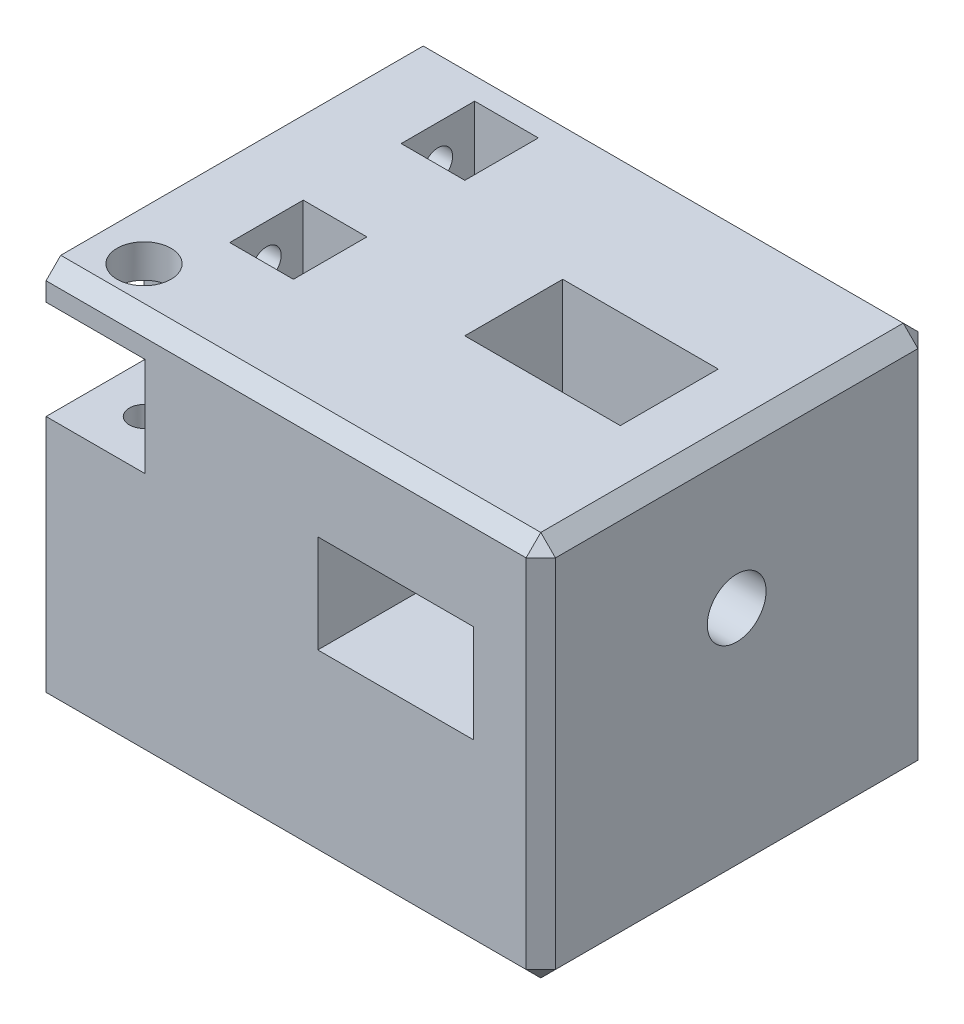
SolidWorks part; units mm, degrees
ref_plane "Front Plane" through (0, 0, 0) normal (1, 0, 0) x (0, 1, 0)
ref_plane "Top Plane" through (0, 0, 0) normal (0, 0, 1) x (0, 1, 0)
ref_plane "Right Plane" through (0, 0, 0) normal (0, 1, 0) x (-1, 0, 0)
sketch "Sketch1" plane through (0, 0, 0) normal (1, 0, 0) x (0, 1, 0)
  line L1 (-640.9609, 1222.3293) -> (-562.1826, 1222.3293)
  line L2 (-640.9609, 1222.3293) -> (-640.9609, 1142.3293)
  line L3 (-640.9609, 1142.3293) -> (-562.1826, 1142.3293)
  line L4 (-562.1826, 1222.3293) -> (-562.1826, 1142.3293)
  line L5 (-640.9609, 1794.8731) -> (-640.9609, 1906.8731) construction
  line L6 (-519.5399, 1142.3293) -> (-1295.5399, 1142.3293) construction
  line L7 (-562.1826, 1906.8731) -> (-562.1826, 1794.8731) construction
  dimension "D1" = 20
extrude "Boss-Extrude1" add sketch "Sketch1" along normal blind 45
sketch "Sketch2" plane through (0, 0, 1222.3293) normal (0, 0, 1) x (1, 0, 0)
  line L4 (0, -562.1826) -> (0, -640.9609)
  line L5 (0, -640.9609) -> (45, -640.9609)
  line L6 (45, -640.9609) -> (45, -562.1826)
  line L7 (45, -562.1826) -> (0, -562.1826)
  line L8 (0, -562.1826) -> (0, -640.9609)
  line L9 (0, -640.9609) -> (45, -640.9609) construction
  line L10 (45, -640.9609) -> (45, -562.1826) construction
  line L11 (45, -562.1826) -> (0, -562.1826) construction
  line L12 (0, -568.9825) -> (20.2, -568.9825)
  line L13 (0, -568.9825) -> (0, -589.1825)
  line L14 (0, -589.1825) -> (20.2, -589.1825)
  line L15 (20.2, -568.9825) -> (20.2, -589.1825)
  dimension "D2" = 20.2
  dimension "D3" = 20.2
  dimension "D1" = 0
extrude "Cut-Extrude1" cut sketch "Sketch2" against normal blind 20 contours L15 L12 L8 L14
sketch "Sketch3" plane through (0, -562.1826, 0) normal (0, 1, 0) x (-1, 0, 0)
  line L0 (-45, 1222.3293) -> (0, 1222.3293) construction
  line L1 (-11.1022, 1202.3293) -> (-8.8978, 1222.2368) construction
  line L2 (-10, 1252.7778) -> (-10, 1171.7883) construction
  line L5 (-11.1022, 1202.3293) -> (-8.8978, 1202.3293)
  line L6 (-8.8978, 1202.3293) -> (-8.8978, 1811.9293)
  line L7 (-8.8978, 1811.9293) -> (-11.1022, 1811.9293)
  line L8 (-11.1022, 1811.9293) -> (-11.1022, 1202.3293)
  line L9 (-11.1022, 1202.3293) -> (-8.8978, 1202.3293)
  line L10 (-8.8978, 1202.3293) -> (-8.8978, 1811.9293)
  line L11 (-8.8978, 1811.9293) -> (-11.1022, 1811.9293)
  line L12 (-11.1022, 1811.9293) -> (-11.1022, 1202.3293)
  circle A0 centre (-10, 1212.3293) radius 3
  point P12 (-10, 1212.283)
  dimension "D1" = 6
  dimension "D2" = 10
  dimension "D3" = 0
extrude "Cut-Extrude2" cut sketch "Sketch3" against normal through all both and the other way through all contours L12 A0 | L12 A0 L10 | L10 A0
sketch "Sketch4" plane through (45, 0, 0) normal (1, 0, 0) x (0, 1, 0)
  line L4 (-640.9609, 1222.3293) -> (-640.9609, 1142.3293)
  line L5 (-640.9609, 1142.3293) -> (-562.1826, 1142.3293)
  line L6 (-562.1826, 1142.3293) -> (-562.1826, 1222.3293)
  line L7 (-562.1826, 1222.3293) -> (-640.9609, 1222.3293)
  line L8 (-640.9609, 1222.3293) -> (-640.9609, 1142.3293)
  line L9 (-640.9609, 1142.3293) -> (-562.1826, 1142.3293)
  line L10 (-562.1826, 1142.3293) -> (-562.1826, 1222.3293)
  line L15 (-562.1826, 1222.3293) -> (-640.9609, 1222.3293)
  dimension "D1" = 0
extrude "Boss-Extrude2" add sketch "Sketch4" along normal blind 56
sketch "Sketch5" plane through (101, 0, 0) normal (1, 0, 0) x (0, 1, 0)
  circle A0 centre (-592.5449, 1182.3293) radius 10
extrude "Cut-Extrude3" cut sketch "Sketch5" against normal up to surface and the other way through all
ref_plane "Plane1" through (57.2302, 0, 0) normal (-1, 0, 0) x (0, -1, 0)
sketch "Sketch6" plane through (57.2302, 0, 0) normal (-1, 0, 0) x (0, -1, 0)
  circle A0 centre (592.5449, 1182.3293) radius 3.4
  dimension "D1" = 6.8
extrude "Boss-Extrude3" add sketch "Sketch6" along normal blind 12
sketch "Sketch7" plane through (50.4802, 0, 0) normal (1, 0, 0) x (0, 1, 0)
  circle A1 centre (-592.5449, 1182.3293) radius 10
  circle A2 centre (-592.5449, 1182.3293) radius 10
  dimension "D1" = 0
extrude "Boss-Extrude4" add sketch "Sketch7" along normal blind 5
ref_plane "Plane2" through (85.7302, 0, 0) normal (1, 0, 0) x (0, 1, 0)
sketch "Sketch8" plane through (85.7302, 0, 0) normal (1, 0, 0) x (0, 1, 0)
  circle A0 centre (-592.5449, 1182.3293) radius 3.4
extrude "Boss-Extrude5" add sketch "Sketch8" along normal blind 1.5 separate body
sketch "Sketch9" plane through (87.2302, 0, 0) normal (1, 0, 0) x (0, 1, 0)
  circle A0 centre (-592.5449, 1182.3293) radius 10
extrude "Boss-Extrude6" add sketch "Sketch9" along normal up to surface (13.7698 mm away)
sketch "Sketch10" plane through (0, 0, 1222.3293) normal (0, 0, 1) x (1, 0, 0)
  line L0 (87.4802, -585.1449) -> (51.7302, -600.2949) construction
  line L1 (51.4802, -600.0449) -> (51.9802, -600.5449) construction
  line L2 (49.9802, -581.5599) -> (49.9802, -603.5299) construction
  line L3 (89.2302, -602.7199) -> (49.9802, -602.7199)
  line L4 (89.2302, -602.7199) -> (89.2302, -582.7199)
  line L5 (89.2302, -582.7199) -> (49.9802, -582.7199)
  line L6 (49.9802, -602.7199) -> (49.9802, -582.7199)
  line L7 (89.2302, -602.7199) -> (49.9802, -582.7199) construction
  line L8 (89.2302, -582.7199) -> (49.9802, -602.7199) construction
  line L10 (55.4802, -582.7199) -> (49.9802, -582.7199)
  line L11 (55.4802, -582.7199) -> (55.4802, -602.7199)
  line L12 (55.4802, -602.7199) -> (49.9802, -602.7199)
  line L13 (49.9802, -582.7199) -> (49.9802, -602.7199)
  line L14 (89.2302, -582.7199) -> (87.2302, -582.7199)
  line L15 (89.2302, -582.7199) -> (89.2302, -602.7199)
  line L16 (89.2302, -602.7199) -> (87.2302, -602.7199)
  line L17 (87.2302, -582.7199) -> (87.2302, -602.7199)
  point P6 (69.6052, -592.7199)
  dimension "D1" = 20
  dimension "D2" = 5.5
  dimension "D3" = 2
extrude "Cut-Extrude4" cut sketch "Sketch10" against normal blind 41 contours L5 L11 L3 L4
sketch "Sketch13" plane through (55.4802, 0, 0) normal (1, 0, 0) x (0, 1, 0)
  line L1 (-562.1826, 1192.3293) -> (-592.5449, 1192.3293)
  line L2 (-562.1826, 1192.3293) -> (-562.1826, 1172.3293)
  line L3 (-562.1826, 1172.3293) -> (-592.5449, 1172.3293)
  line L4 (-592.5449, 1192.3293) -> (-592.5449, 1172.3293)
  line L5 (-562.1826, 1142.3293) -> (-562.1826, 1222.3293) construction
  arc A0 (-602.4948, 1181.3293) -> (-582.7199, 1184.1919) centre (-592.5449, 1182.3293) ccw construction
  arc A1 (-602.4948, 1181.3293) -> (-582.7199, 1184.1919) centre (-592.5449, 1182.3293) ccw
  dimension "D1" = 20
extrude "Cut-Extrude5" cut sketch "Sketch13" along normal up to surface (31.75 mm away) contours L1 L4 L3 L2
sketch "Sketch11" plane through (57.2302, 0, 0) normal (1, 0, 0) x (0, 1, 0)
  circle A0 centre (-592.5449, 1182.3293) radius 3.4
  arc A1 (-595.7945, 1181.3293) -> (-592.5449, 1178.9293) centre (-592.5449, 1182.3293) ccw construction
extrude "Boss-Extrude7" add sketch "Sketch11" against normal blind 14
sketch "Sketch12" plane through (85.7302, 0, 0) normal (-1, 0, 0) x (0, -1, 0)
  circle A1 centre (592.5449, 1182.3293) radius 3.4
  circle A2 centre (592.5449, 1182.3293) radius 3.4
  dimension "D1" = 0
extrude "Boss-Extrude8" add sketch "Sketch12" against normal up to surface (1.5 mm away) up to face at (87.2302, -593.7598, 1180.351)
sketch "Sketch14" plane through (57.2302, 0, 0) normal (1, 0, 0) x (0, 1, 0)
  circle A0 centre (-592.5449, 1182.3293) radius 2.5
  circle A1 centre (-592.5449, 1182.3293) radius 3.4
  circle A2 centre (-592.5449, 1182.3293) radius 3.4
  dimension "D2" = 5
  dimension "D1" = 0
extrude "Cut-Extrude6" cut sketch "Sketch14" against normal through all both and the other way through all contours A0
sketch "Sketch15" plane through (101, 0, 0) normal (1, 0, 0) x (0, 1, 0)
  circle A0 centre (-592.5449, 1182.3293) radius 6
  dimension "D1" = 12
extrude "Cut-Extrude7" cut sketch "Sketch15" against normal blind 10 and the other way through all
sketch "Sketch16" plane through (0, 0, 0) normal (-1, 0, 0) x (0, -1, 0)
  line L1 (589.9468, 1177.8293) -> (595.143, 1177.8293)
  line L2 (595.143, 1177.8293) -> (597.7411, 1182.3293)
  line L3 (597.7411, 1182.3293) -> (595.143, 1186.8293)
  line L4 (595.143, 1186.8293) -> (589.9468, 1186.8293)
  line L5 (589.9468, 1186.8293) -> (587.3488, 1182.3293)
  line L6 (587.3488, 1182.3293) -> (589.9468, 1177.8293)
  circle A0 centre (592.5449, 1182.3293) radius 4.5 construction
  dimension "D1" = 9
extrude "Cut-Extrude8" cut sketch "Sketch16" against normal blind 45
sketch "Sketch17" plane through (0, 0, 0) normal (-1, 0, 0) x (0, -1, 0)
  line L0 (562.1826, 1142.3293) -> (562.1826, 1222.3293) construction
  line L1 (569.6826, 1192.3293) -> (569.6826, 1157.3293) construction
  line L2 (569.6826, 1157.3293) -> (633.4609, 1157.3293) construction
  line L3 (640.9609, 1222.3293) -> (640.9609, 1142.3293) construction
  line L4 (640.9609, 1142.3293) -> (562.1826, 1142.3293) construction
  line L5 (633.4609, 1192.3293) -> (633.4609, 1157.3293) construction
  line L6 (569.6826, 1192.3293) -> (633.4609, 1192.3293) construction
  circle A0 centre (569.6826, 1157.3293) radius 3
  circle A1 centre (633.4609, 1157.3293) radius 3
  circle A2 centre (569.6826, 1192.3293) radius 3
  circle A3 centre (633.4609, 1192.3293) radius 3
  dimension "D1" = 6
  dimension "D2" = 7.5
  dimension "D3" = 7.5
  dimension "D4" = 15
  dimension "D5" = 50
extrude "Cut-Extrude9" cut sketch "Sketch17" against normal blind 45
sketch "Sketch18" plane through (0, -562.1826, 0) normal (0, 1, 0) x (-1, 0, 0)
  line L1 (-28, 1149.8293) -> (-15, 1149.8293)
  line L2 (-28, 1149.8293) -> (-28, 1164.8293)
  line L3 (-28, 1164.8293) -> (-15, 1164.8293)
  line L4 (-15, 1149.8293) -> (-15, 1164.8293)
  line L5 (-28, 1184.8293) -> (-15, 1184.8293)
  line L6 (-28, 1184.8293) -> (-28, 1199.8293)
  line L7 (-28, 1199.8293) -> (-15, 1199.8293)
  line L8 (-15, 1184.8293) -> (-15, 1199.8293)
  line L9 (0, 1142.3293) -> (0, 1222.3293) construction
  line L10 (-101, 1142.3293) -> (0, 1142.3293) construction
  point P11 (-15, 1192.3293)
  point P14 (-15, 1157.3293)
  dimension "D1" = 13
  dimension "D2" = 15
  dimension "D3" = 50
  dimension "D4" = 15
  dimension "D5" = 15
extrude "Cut-Extrude10" cut sketch "Sketch18" against normal blind 21
sketch "Sketch19" plane through (0, -640.9609, 0) normal (0, -1, 0) x (1, 0, 0)
  line L4 (28, 1149.8293) -> (28, 1164.8293)
  line L5 (15, 1149.8293) -> (28, 1149.8293)
  line L6 (15, 1164.8293) -> (15, 1149.8293)
  line L7 (28, 1164.8293) -> (15, 1164.8293)
  line L8 (28, 1149.8293) -> (28, 1164.8293)
  line L9 (15, 1149.8293) -> (28, 1149.8293)
  line L10 (15, 1164.8293) -> (15, 1149.8293)
  line L11 (28, 1164.8293) -> (15, 1164.8293)
  line L12 (28, 1184.8293) -> (28, 1199.8293)
  line L13 (15, 1184.8293) -> (28, 1184.8293)
  line L14 (15, 1199.8293) -> (15, 1184.8293)
  line L15 (28, 1199.8293) -> (15, 1199.8293)
  line L16 (28, 1184.8293) -> (28, 1199.8293)
  line L17 (15, 1184.8293) -> (28, 1184.8293)
  line L18 (15, 1199.8293) -> (15, 1184.8293)
  line L19 (28, 1199.8293) -> (15, 1199.8293)
  dimension "D1" = 0
  dimension "D2" = 0
extrude "Cut-Extrude11" cut sketch "Sketch19" against normal blind 21
chamfer "Chamfer1" distance 3 angle 45 8 edges at (101, -601.5717, 1142.3293) (50.5, -640.9609, 1142.3293) (50.5, -640.9609, 1222.3293) (50.5, -562.1826, 1142.3293) (101, -640.9609, 1182.3293) (101, -601.5717, 1222.3293) (101, -562.1826, 1182.3293) (50.5, -562.1826, 1222.3293)
sketch "Sketch20" plane through (0, -562.1826, 0) normal (0, 1, 0) x (-1, 0, 0)
  circle A0 centre (-10, 1212.3293) radius 5.5
  dimension "D1" = 11
extrude "Cut-Extrude12" cut sketch "Sketch20" against normal blind 8
sketch "Sketch21" plane through (0, -640.9609, 0) normal (0, -1, 0) x (1, 0, 0)
  circle A0 centre (10, 1212.3293) radius 5.5
  dimension "D1" = 11
extrude "Cut-Extrude13" cut sketch "Sketch21" against normal blind 8
